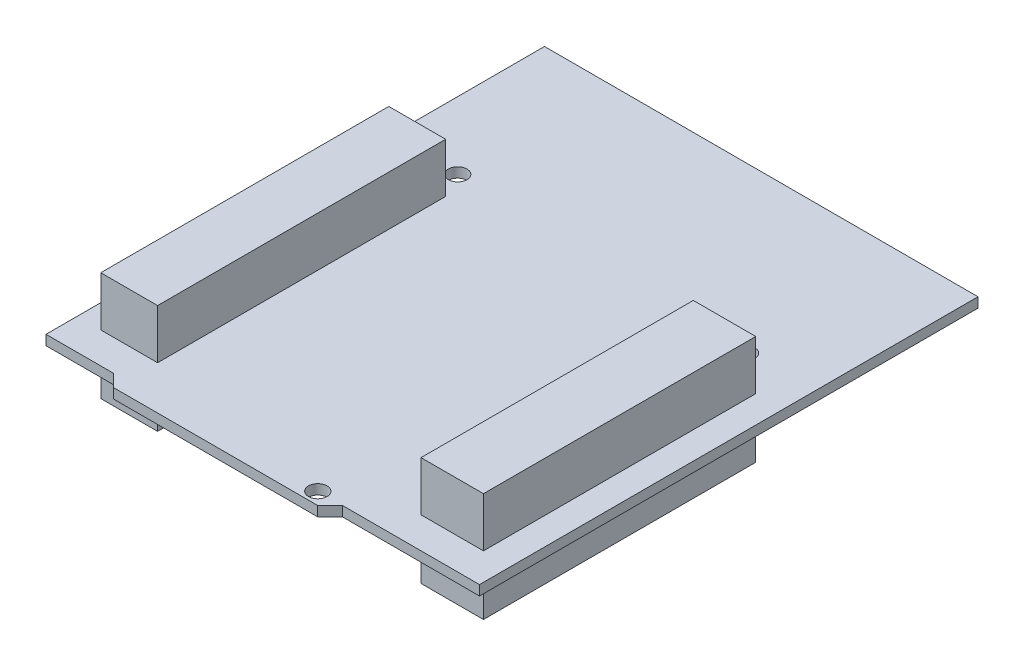
SolidWorks part; units mm, degrees
ref_plane "Front Plane" through (0, 0, 0) normal (0, 0, 1) x (1, 0, 0)
ref_plane "Top Plane" through (0, 0, 0) normal (0, 1, 0) x (1, 0, 0)
ref_plane "Right Plane" through (0, 0, 0) normal (1, 0, 0) x (0, 0, -1)
sketch "Sketch1" plane through (0, 0, 0) normal (0, 1, 0) x (1, 0, 0)
  line L0 (0, 0) -> (10.87, 0)
  line L1 (12.87, -2) -> (45.87, -2)
  line L2 (0, 0) -> (0, 80.5)
  line L3 (0, 80.5) -> (70, 80.5)
  line L4 (70, 0) -> (70, 80.5)
  line L5 (10.87, 0) -> (12.87, -2)
  line L7 (45.87, -2) -> (47.87, 0)
  line L8 (47.87, 0) -> (70, 0)
  circle A0 centre (10.87, 55.61) radius 1.5
  circle A1 centre (59.13, 53.84) radius 1.5
  circle A2 centre (43.89, 0) radius 1.5
  dimension "D3" = 3
  dimension "D4" = 3
  dimension "D5" = 3
  dimension "D1" = 70
  dimension "D2" = 82.5
  dimension "D6" = 10.87
  dimension "D7" = 48.26
  dimension "D8" = 33.02
  dimension "D9" = 33
  dimension "D10" = 2
  dimension "D11" = 57.61
  dimension "D12" = 55.84
extrude "Boss-Extrude1" add sketch "Sketch1" along normal blind 1.6
sketch "Sketch2" plane through (0, 1.6, 0) normal (0, 1, 0) x (1, 0, 0)
  line L0 (3.8125, 51.5439) -> (12.9919, 51.5439)
  line L1 (3.8125, 51.5439) -> (12.9919, 51.5439)
  line L2 (3.8125, 51.5439) -> (3.8125, 5.0311)
  line L3 (3.8125, 5.0311) -> (12.9919, 5.0311)
  line L4 (12.9919, 51.5439) -> (12.9919, 5.0311)
  line L5 (55.5272, 49.0009) -> (65.6083, 49.0009)
  line L6 (55.5272, 49.0009) -> (55.5272, 5.0311)
  line L7 (55.5272, 5.0311) -> (65.6083, 5.0311)
  line L8 (65.6083, 49.0009) -> (65.6083, 5.0311)
  line L9 (12.9919, 51.5439) -> (12.9919, 5.0311)
  line L10 (3.8125, 5.0311) -> (12.9919, 5.0311)
  line L11 (3.8125, 51.5439) -> (3.8125, 5.0311)
  line L12 (55.5272, 49.0009) -> (55.5272, 5.0311)
  line L13 (55.5272, 5.0311) -> (65.6083, 5.0311)
  line L14 (65.6083, 49.0009) -> (65.6083, 5.0311)
  line L15 (55.5272, 49.0009) -> (65.6083, 49.0009)
  dimension "D2" = 0
extrude "Boss-Extrude2" add sketch "Sketch2" along normal blind 8 and the other way blind 9.6 contours L4 L3 L2 L1 | L6 L7 L8 L5
